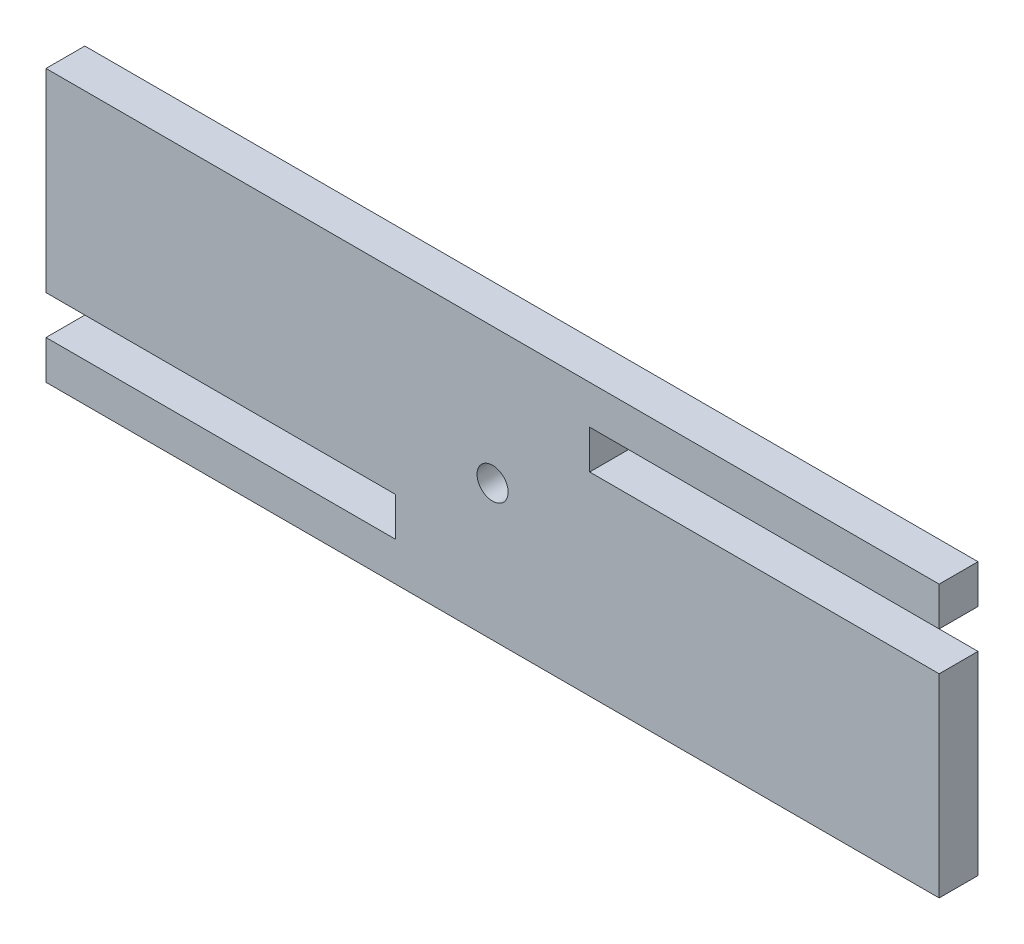
SolidWorks part; units mm, degrees
ref_plane "Front Plane" through (0, 0, 0) normal (0, 0, 1) x (1, 0, 0)
ref_plane "Top Plane" through (0, 0, 0) normal (0, 1, 0) x (1, 0, 0)
ref_plane "Right Plane" through (0, 0, 0) normal (1, 0, 0) x (0, 0, -1)
sketch "Sketch1" plane through (0, 0, 0) normal (0, 0, 1) x (1, 0, 0)
  line L0 (-115, 35) -> (115, 35)
  line L1 (115, 35) -> (115, 25)
  line L2 (115, -35) -> (-115, -35)
  line L3 (-115, -35) -> (-115, -25)
  line L4 (-115, 0) -> (115, 0) construction
  line L5 (0, 35) -> (0, -35) construction
  line L6 (-115, -25) -> (-25, -25)
  line L7 (-25, -25) -> (-25, -15)
  line L8 (-25, -15) -> (-115, -15)
  line L9 (115, 25) -> (25, 25)
  line L10 (25, 25) -> (25, 15)
  line L11 (25, 15) -> (115, 15)
  line L12 (-115, -15) -> (-115, 35)
  line L13 (115, 15) -> (115, -35)
  circle A0 centre (0, 0) radius 4
  point P8 (0, 0)
  dimension "D3" = 8
  dimension "D1" = 70
  dimension "D2" = 230
  dimension "D4" = 10
  dimension "D5" = 10
  dimension "D6" = 10
  dimension "D7" = 10
  dimension "D8" = 90
  dimension "D9" = 90
  dimension "D10" = 35
extrude "Boss-Extrude2" add sketch "Sketch1" along normal blind 10
